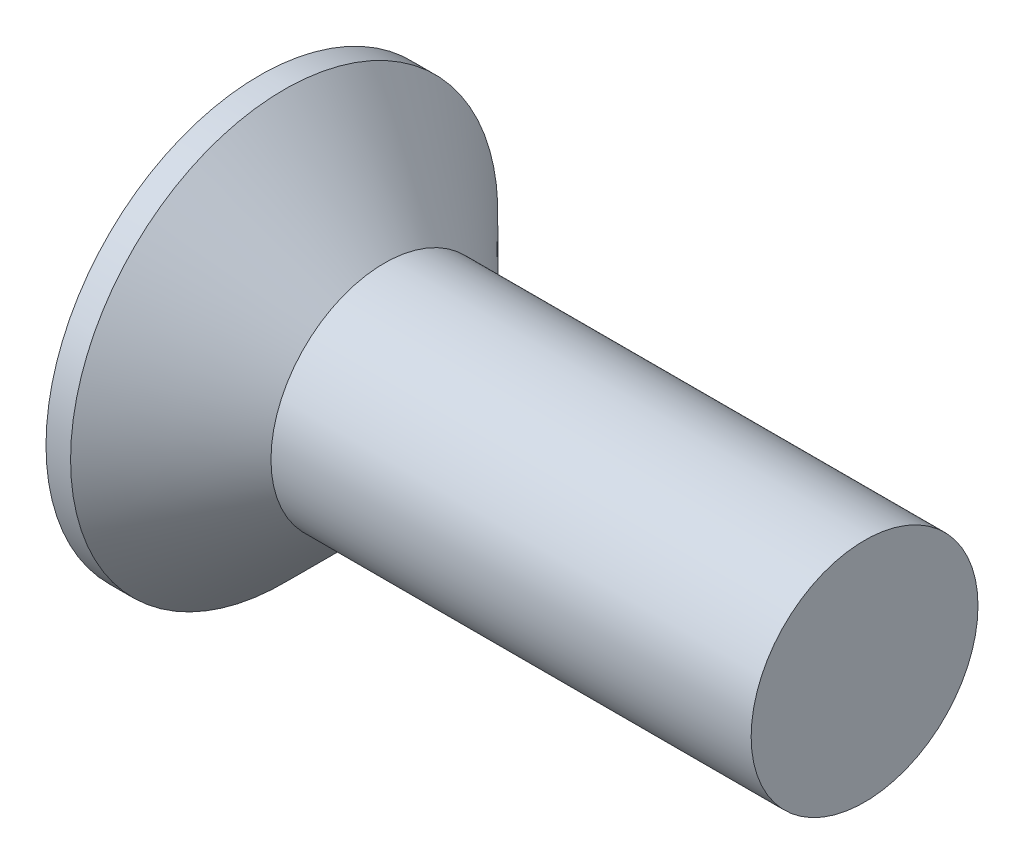
SolidWorks part; units mm, degrees
ref_plane "Plan de face" through (0, 0, 0) normal (0, 0, 1) x (1, 0, 0)
ref_plane "Plan de dessus" through (0, 0, 0) normal (0, 1, 0) x (1, 0, 0)
ref_plane "Plan de droite" through (0, 0, 0) normal (1, 0, 0) x (0, 0, -1)
sketch "Esquisse1" plane through (0, 0, 0) normal (0, 0, 1) x (1, 0, 0)
  line L0 (0, 0) -> (16, 0)
  line L1 (16, 0) -> (16, 3)
  line L2 (16, 3) -> (3.3, 3)
  line L4 (0, 5.65) -> (0, 0)
  line L5 (0, 5.65) -> (0.65, 5.65)
  line L6 (0.65, 5.65) -> (3.3, 3)
  point P3 (0, 5.65)
  point P8 (0, 5.65)
  dimension "D1" = 16
  dimension "D2" = 3
  dimension "D3" = 5.65
  dimension "D4" = 3.3
  dimension "D5" = 45
revolve "Révolution1" add sketch "Esquisse1" angle 360 about L0
equation "\"D3@Esquisse1\"=11.3/2"
